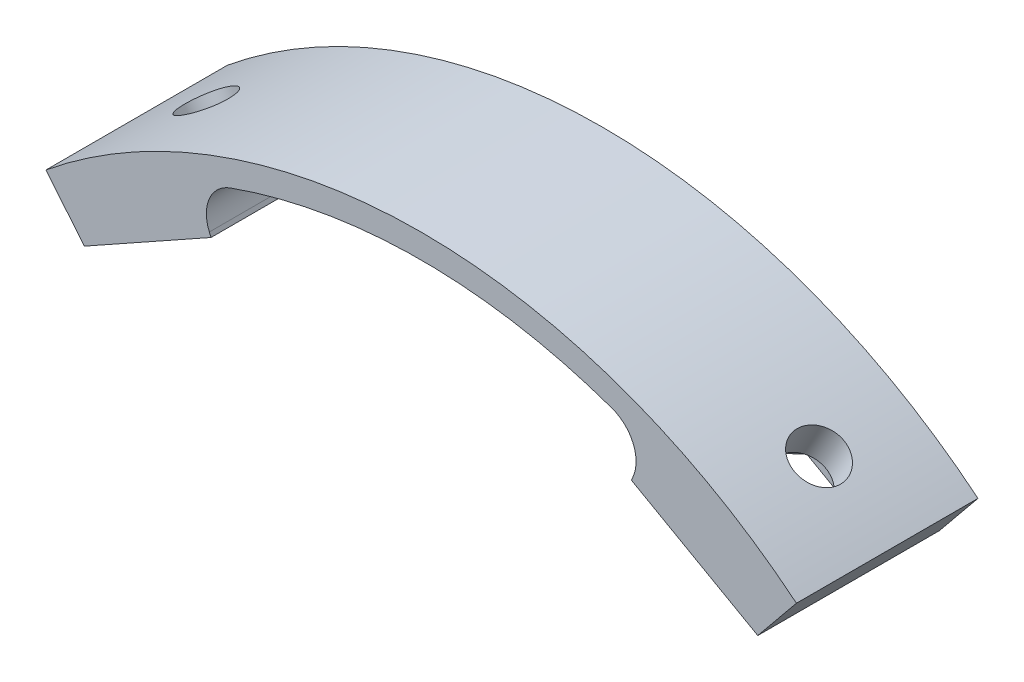
SolidWorks part; units mm, degrees
ref_plane "Спереди" through (0, 0, 0) normal (0, 0, 1) x (1, 0, 0)
ref_plane "Сверху" through (0, 0, 0) normal (0, 1, 0) x (1, 0, 0)
ref_plane "Справа" through (0, 0, 0) normal (1, 0, 0) x (0, 0, -1)
sketch "Эскиз1" plane through (0, 0, 0) normal (0, 0, 1) x (1, 0, 0)
  line L0 (-3.7428, -26.0762) -> (-3.7428, 22.9238) construction
  line L3 (-3.7428, -26.0762) -> (-3.1437, -26.0762) construction
  line L4 (-3.7428, -26.0762) -> (36.9537, -26.0762) construction
  line L5 (-34.7428, 11.8711) -> (-33.4775, 10.3222)
  line L6 (25.9919, 10.3222) -> (27.2572, 11.8711)
  line L7 (-33.4775, 10.3222) -> (-31.5795, 7.9989)
  line L8 (25.9919, 10.3222) -> (24.0627, 7.9607)
  line L9 (-21.106, 13.8561) -> (-22.4842, 17.0255)
  line L10 (-31.5795, 7.9989) -> (-21.106, 13.8561)
  line L11 (13.6204, 13.8561) -> (14.9986, 17.0255)
  line L12 (13.6204, 13.8561) -> (24.0627, 7.9607)
  line L13 (-3.7428, -26.0762) -> (23.3847, 20.91) construction
  line L14 (-3.7428, -26.0762) -> (-31.7012, 22.3492) construction
  arc A0 (-34.7428, 11.8711) -> (27.2572, 11.8711) centre (-3.7428, -26.0762) cw
  arc A2 (-22.4842, 17.0255) -> (14.9986, 17.0255) centre (-3.7428, -26.0762) cw
  arc A5 (-33.4775, 10.3222) -> (25.9919, 10.3222) centre (-3.7428, -26.0762) cw construction
  point P19 (17.913, 11.4326)
  point P20 (0, 0)
  point P21 (-25.4085, 11.4499)
  dimension "D1" = 49
  dimension "D4" = 2
  dimension "D5" = 30
  dimension "D7" = 30
  dimension "D2" = 62
  dimension "D3" = 90
  dimension "D6" = 12
extrude "Бобышка-Вытянуть2" add sketch "Эскиз1" along normal blind 15
sketch "Эскиз6" plane through (9.224, 16.3382, 0) normal (-0.4916, -0.8708, 0) x (0.8708, -0.4916, 0)
  line L0 (17.8996, 0) -> (-36.0904, 0) construction
  line L1 (5.0488, 15) -> (5.0488, 0) construction
  circle A0 centre (11.0488, 7.5) radius 2.1
  point P0 (9.9781, 0)
  point P6 (11.0259, 7.5)
  point P7 (11.5387, 7.5)
  point P8 (0, 0)
  point P9 (0, 0)
  point P10 (10.682, 7.5)
  dimension "D1" = 4.2
  dimension "D2" = 7.5
  dimension "D3" = 6
sketch "Эскиз7" plane through (-10.931, 19.5463, 0) normal (0.4881, -0.8728, 0) x (0.8728, 0.4881, 0)
  line L0 (-11.6581, 15) -> (-11.6581, 0) construction
  circle A0 centre (-17.6581, 7.4091) radius 2.1
  point P0 (-17.218, -0.078)
  point P1 (0, 0)
  point P4 (-16.5877, 0)
  dimension "D2" = 4.2
  dimension "D1" = 7.5
  dimension "D3" = 6
fillet "Скругление2" radius 3 2 edges at (14.9986, 17.0255, 7.5) (-22.4842, 17.0255, 7.5)
extrude "Вырез-Вытянуть5" cut sketch "Эскиз6" against normal blind 13.55
extrude "Вырез-Вытянуть6" cut sketch "Эскиз7" against normal blind 13.55
sketch "Эскиз8" plane through (-10.931, 19.5463, 0) normal (0.4881, -0.8728, 0) x (0.8728, 0.4881, 0)
  line L0 (29.5841, 0) -> (-24.529, 0) construction
  line L1 (-19.7077, 3.8591) -> (-15.6085, 3.8591)
  line L2 (-15.6085, 3.8591) -> (-13.5589, 7.4091)
  line L3 (-13.5589, 7.4091) -> (-15.6085, 10.9591)
  line L4 (-15.6085, 10.9591) -> (-19.7077, 10.9591)
  line L5 (-19.7077, 10.9591) -> (-21.7573, 7.4091)
  line L6 (-21.7573, 7.4091) -> (-19.7077, 3.8591)
  circle A0 centre (-17.6581, 7.4091) radius 3.55 construction
  dimension "D1" = 7.1
  dimension "D2" = 60
extrude "Вырез-Вытянуть7" cut sketch "Эскиз8" against normal blind 2.55
sketch "Эскиз9" plane through (9.224, 16.3382, 0) normal (-0.4916, -0.8708, 0) x (0.8708, -0.4916, 0)
  line L0 (17.8996, 0) -> (-36.0904, 0) construction
  line L1 (8.9992, 3.95) -> (13.0983, 3.95)
  line L2 (13.0983, 3.95) -> (15.1479, 7.5)
  line L3 (15.1479, 7.5) -> (13.0983, 11.05)
  line L4 (13.0983, 11.05) -> (8.9992, 11.05)
  line L5 (8.9992, 11.05) -> (6.9496, 7.5)
  line L6 (6.9496, 7.5) -> (8.9992, 3.95)
  circle A0 centre (11.0488, 7.5) radius 3.55 construction
  dimension "D1" = 7.1
  dimension "D2" = 60
extrude "Вырез-Вытянуть8" cut sketch "Эскиз9" against normal blind 2.55
